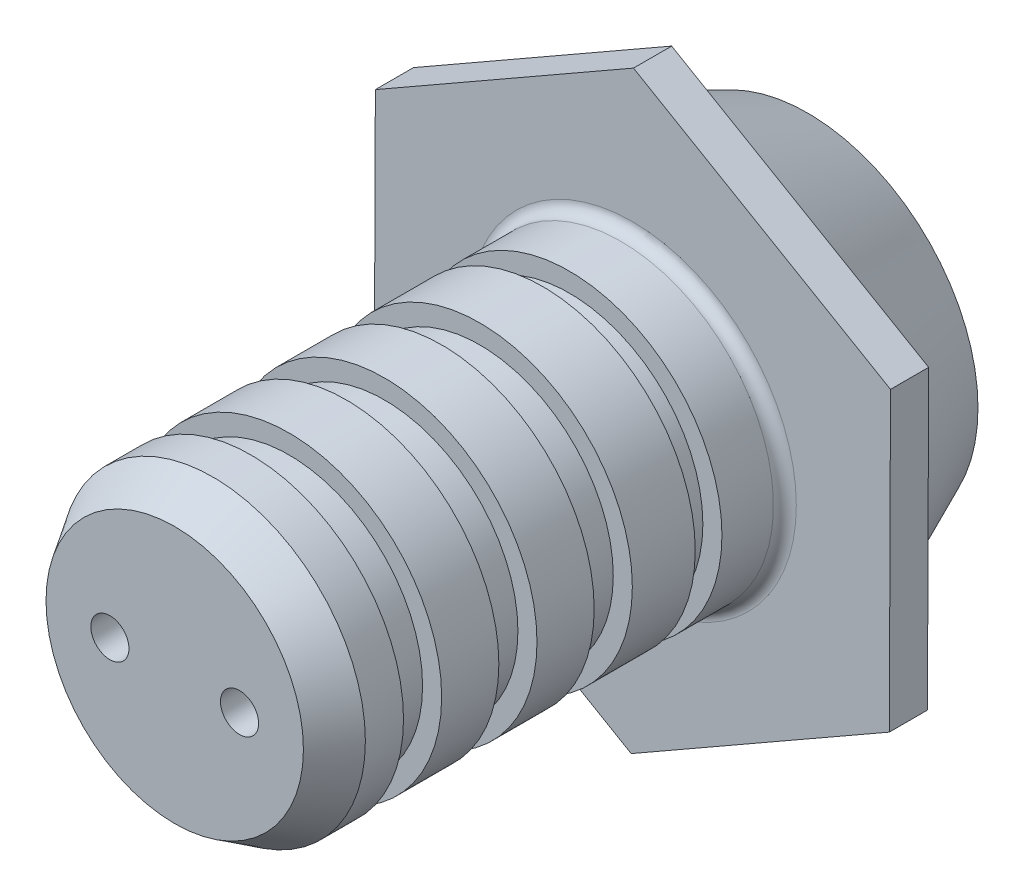
SolidWorks part; units mm, degrees
ref_plane "Front Plane" through (0, 0, 0) normal (0, 0, 1) x (1, 0, 0)
ref_plane "Top Plane" through (0, 0, 0) normal (0, 1, 0) x (1, 0, 0)
ref_plane "Right Plane" through (0, 0, 0) normal (1, 0, 0) x (0, 0, -1)
sketch "Sketch1" plane through (0, 0, 0) normal (0, 0, 1) x (1, 0, 0)
  circle A0 centre (0, 0) radius 4
  dimension "D1" = 8
extrude "Boss-Extrude1" add sketch "Sketch1" along normal blind 11
ref_plane "Plane6" through (0, 0, 2) normal (0, 0, 1) x (1, 0, 0)
ref_plane "Plane7" through (0, 0, 4.5) normal (0, 0, 1) x (1, 0, 0)
ref_plane "Plane8" through (0, 0, 7) normal (0, 0, 1) x (1, 0, 0)
ref_plane "Plane9" through (0, 0, 9.5) normal (0, 0, 1) x (1, 0, 0)
ref_plane "Plane10" through (0, 0, 12) normal (0, 0, 1) x (1, 0, 0)
sketch "Sketch9" plane through (0, 0, 2) normal (0, 0, 1) x (1, 0, 0)
  circle A0 centre (0, 0) radius 4
  circle A1 centre (0, 0) radius 3.5
extrude "Cut-Extrude6" cut sketch "Sketch9" against normal mid plane 0.7
sketch "Sketch10" plane through (0, 0, 4.5) normal (0, 0, 1) x (1, 0, 0)
  circle A0 centre (0, 0) radius 4 construction
  circle A1 centre (0, 0) radius 3.5 construction
  circle A2 centre (0, 0) radius 4
  circle A3 centre (0, 0) radius 3.5
extrude "Cut-Extrude7" cut sketch "Sketch10" against normal mid plane 1
sketch "Sketch11" plane through (0, 0, 7) normal (0, 0, 1) x (1, 0, 0)
  circle A0 centre (0, 0) radius 4 construction
  circle A1 centre (0, 0) radius 3.5 construction
  circle A2 centre (0, 0) radius 4
  circle A3 centre (0, 0) radius 3.5
extrude "Cut-Extrude8" cut sketch "Sketch11" against normal mid plane 1
sketch "Sketch12" plane through (0, 0, 9.5) normal (0, 0, 1) x (1, 0, 0)
  circle A0 centre (0, 0) radius 4 construction
  circle A1 centre (0, 0) radius 3.5 construction
  circle A2 centre (0, 0) radius 4
  circle A3 centre (0, 0) radius 3.5
extrude "Cut-Extrude9" cut sketch "Sketch12" against normal mid plane 1
sketch "Sketch15" plane through (0, 0, 0) normal (0, 0, -1) x (-1, 0, 0)
  line L1 (6.739, 3.9262) -> (-0.0307, 7.7992)
  line L2 (-0.0307, 7.7992) -> (-6.7697, 3.873)
  line L3 (-6.7697, 3.873) -> (-6.739, -3.9262)
  line L4 (-6.739, -3.9262) -> (0.0307, -7.7992)
  line L5 (0.0307, -7.7992) -> (6.7697, -3.873)
  line L6 (6.7697, -3.873) -> (6.739, 3.9262)
  circle A0 centre (0, 0) radius 6.7544 construction
extrude "Boss-Extrude5" add sketch "Sketch15" along normal blind 1
fillet "Fillet2" radius 0.3 1 edges at (4, 0, 0)
ref_plane "Plane11" through (0, 0, -1.3) normal (0, 0, 1) x (1, 0, 0)
ref_plane "Plane12" through (0, 0, -1.6) normal (0, 0, 1) x (1, 0, 0)
sketch "Sketch21" plane through (0, 0, 0) normal (0, 1, 0) x (1, 0, 0)
  circle A0 centre (-5.8, 1.3011) radius 0.3
  dimension "D1" = 5.8
  dimension "D2" = 0.6
sketch "Sketch25" plane through (0, 0, -1.3) normal (0, 0, 1) x (1, 0, 0)
  circle A0 centre (0, 0) radius 5.8
sweep "Sweep2" add profiles "Sketch21" path "Sketch25"
sketch "Sketch26" plane through (0, 0, -1.6) normal (0, 0, 1) x (1, 0, 0)
  circle A1 centre (0, 0) radius 5.8
  circle A2 centre (0, 0) radius 5.8
  dimension "D1" = 0
extrude "Boss-Extrude6" add sketch "Sketch26" against normal blind 3 draft 24
sketch "Sketch27" plane through (0, 0, 11) normal (0, 0, 1) x (1, 0, 0)
  circle A1 centre (0, 0) radius 4
  circle A2 centre (0, 0) radius 4
  dimension "D1" = 0
extrude "Boss-Extrude7" add sketch "Sketch27" along normal blind 1 draft 32
shell "Shell1" thickness 0.5
sketch "Sketch28" plane through (0, 0, 0) normal (0, 1, 0) x (1, 0, 0)
  line L0 (0, 1.5191) -> (0, 4.7136)
  line L2 (0, 6.9665) -> (0, -1.8262) construction
  line L3 (0, 1.5191) -> (-2.4998, 1.5191)
  ellipse E0 centre (0, 1.5191) end of major axis (0, 4.7136) minor radius 2.4998 (0, 4.7136) -> (-2.4998, 1.5191) ccw
revolve "Revolve2" add sketch "Sketch28" angle 360 about L2
sketch "Sketch29" plane through (0, 0, 12) normal (0, 0, 1) x (1, 0, 0)
  circle A0 centre (-1.7, 0) radius 0.5
  circle A1 centre (1.7, 0) radius 0.5
  dimension "D1" = 1
  dimension "D2" = 1.7
  dimension "D3" = 1.7
extrude "Cut-Extrude11" cut sketch "Sketch29" against normal blind 1
